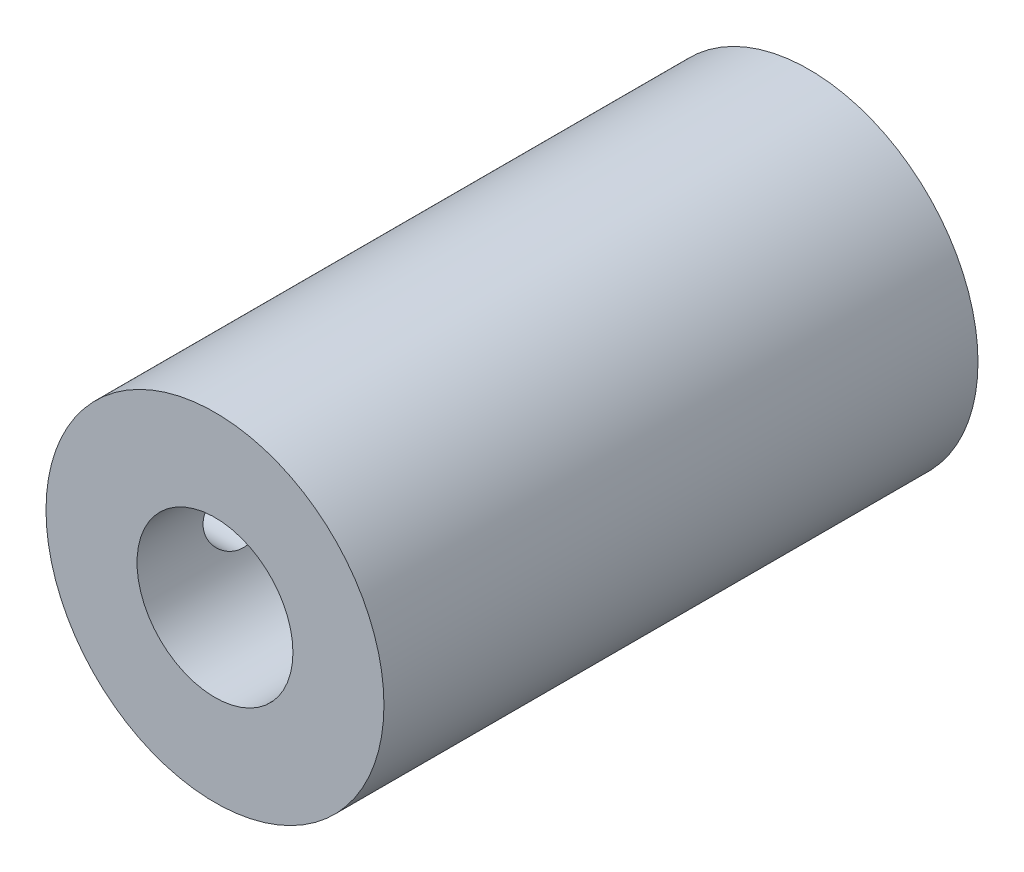
SolidWorks part; units mm, degrees
material "Brass"
ref_plane "Front Plane" through (0, 0, 0) normal (0, 0, 1) x (1, 0, 0)
ref_plane "Top Plane" through (0, 0, 0) normal (0, 1, 0) x (1, 0, 0)
ref_plane "Right Plane" through (0, 0, 0) normal (1, 0, 0) x (0, 0, -1)
sketch "Sketch2" plane through (0, 0, 0) normal (0, 0, 1) x (1, 0, 0)
  circle A0 centre (0, 0) radius 32.512
  circle A1 centre (0, 0) radius 15
  dimension "D1" = 30
  dimension "D2" = 65.024
extrude "Boss-Extrude1" add sketch "Sketch2" along normal mid plane 114.3
sketch "Sketch3" plane through (0, 0, 0) normal (1, 0, 0) x (0, 0, -1)
  line L0 (-57.15, 32.512) -> (-57.15, -32.512) construction
  line L1 (57.15, 32.512) -> (-57.15, 32.512) construction
  circle A0 centre (-38.1, 0) radius 6.35
  dimension "D1" = 12.7
  dimension "D2" = 19.05
  dimension "D3" = 32.512
extrude "Cut-Extrude1" cut sketch "Sketch3" against normal up to next
sketch "Sketch5" plane through (0, 0, 0) normal (0, 1, 0) x (1, 0, 0)
  circle A0 centre (0, 0) radius 3.5
  dimension "D1" = 7
extrude "Cut-Extrude2" cut sketch "Sketch5" against normal up to next
